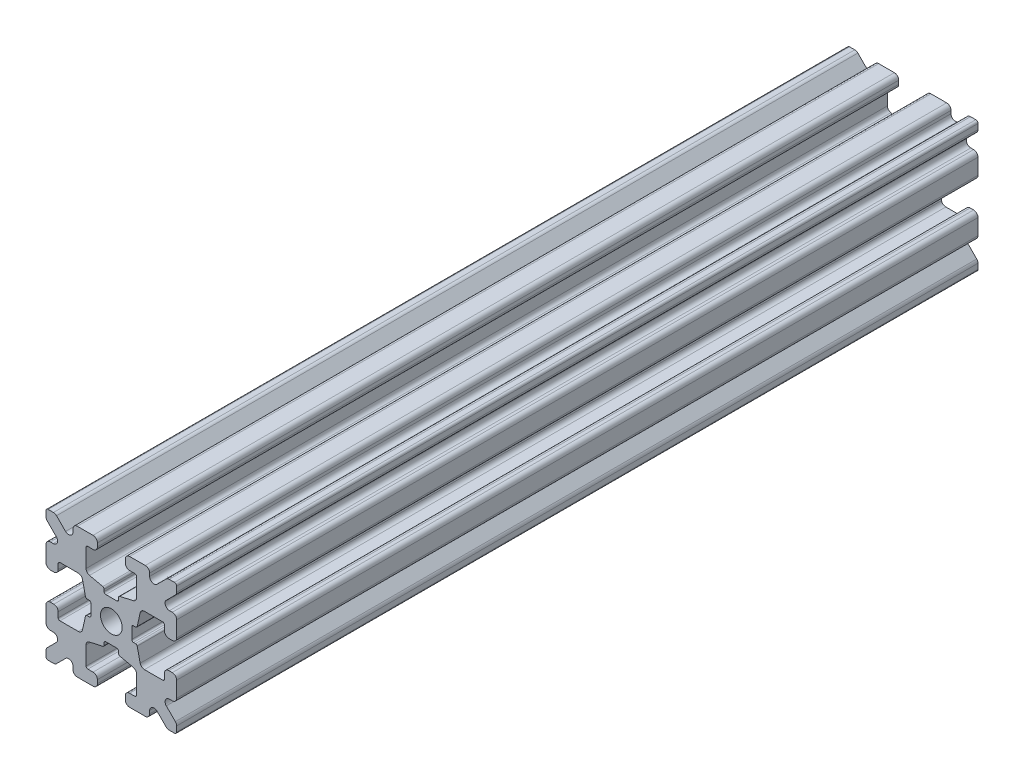
SolidWorks part; units mm, degrees
ref_plane "Front Plane" through (0, 0, 0) normal (0, 0, 1) x (1, 0, 0)
ref_plane "Top Plane" through (0, 0, 0) normal (0, 1, 0) x (1, 0, 0)
ref_plane "Right Plane" through (0, 0, 0) normal (1, 0, 0) x (0, 0, -1)
sketch "Sketch1" plane through (0, 0, 0) normal (0, 0, 1) x (1, 0, 0)
  line L1 (-7.5, -7.5) -> (7.5, -7.5)
  line L2 (-7.5, -7.5) -> (-7.5, 7.5)
  line L3 (-7.5, 7.5) -> (7.5, 7.5)
  line L4 (7.5, -7.5) -> (7.5, 7.5)
  line L5 (-7.5, -7.5) -> (7.5, 7.5) construction
  line L6 (-7.5, 7.5) -> (7.5, -7.5) construction
  circle A0 centre (0, 0) radius 1.25
  point P0 (0, 0)
  dimension "D2" = 2.5
  dimension "D1" = 15
extrude "Boss-Extrude1" add sketch "Sketch1" along normal mid plane 92
fillet "Fillet1" radius 0.25 4 edges at (7.5, -7.5, 0) (-7.5, -7.5, 0) (7.5, 7.5, 0) (-7.5, 7.5, 0)
sketch "Sketch2" plane through (0, 0, 46) normal (0, 0, 1) x (1, 0, 0)
  line L0 (-7.5, 7.25) -> (-7.5, -7.25) construction
  line L1 (-7.5, 1.6) -> (-6.1, 1.6)
  line L2 (-7.5, 1.6) -> (-7.5, -1.6)
  line L3 (-7.5, -1.6) -> (-6.1, -1.6)
  line L4 (-6.1, 1.6) -> (-6.1, 2.9)
  line L5 (0, 0) -> (-12.1036, 0) construction
  line L6 (-6.1, -2.9) -> (-3.4, -2.9)
  line L7 (0, 0) -> (-7.25, 7.25) construction
  line L8 (-6.1, 2.9) -> (-3.4, 2.9)
  line L9 (-3.4, -2.9) -> (-3.4, 2.9)
  line L10 (55, 0) -> (-55, 0) construction
  line L11 (-6.1, -2.9) -> (-6.1, -1.6)
  line L12 (2.9, 6.1) -> (1.6, 6.1)
  line L13 (2.9, 3.4) -> (-2.9, 3.4)
  line L14 (-2.9, 6.1) -> (-2.9, 3.4)
  line L15 (2.9, 6.1) -> (2.9, 3.4)
  line L16 (-1.6, 6.1) -> (-2.9, 6.1)
  line L17 (1.6, 7.5) -> (1.6, 6.1)
  line L18 (-1.6, 7.5) -> (1.6, 7.5)
  line L19 (-1.6, 7.5) -> (-1.6, 6.1)
  line L20 (-1.6, -7.5) -> (-1.6, -6.1)
  line L21 (-1.6, -7.5) -> (1.6, -7.5)
  line L22 (1.6, -7.5) -> (1.6, -6.1)
  line L23 (-1.6, -6.1) -> (-2.9, -6.1)
  line L24 (2.9, -6.1) -> (2.9, -3.4)
  line L25 (-2.9, -6.1) -> (-2.9, -3.4)
  line L26 (2.9, -3.4) -> (-2.9, -3.4)
  line L27 (2.9, -6.1) -> (1.6, -6.1)
  line L28 (6.1, -2.9) -> (6.1, -1.6)
  line L29 (3.4, -2.9) -> (3.4, 2.9)
  line L30 (6.1, 2.9) -> (3.4, 2.9)
  line L31 (6.1, -2.9) -> (3.4, -2.9)
  line L32 (6.1, 1.6) -> (6.1, 2.9)
  line L33 (7.5, -1.6) -> (6.1, -1.6)
  line L34 (7.5, 1.6) -> (7.5, -1.6)
  line L35 (7.5, 1.6) -> (6.1, 1.6)
  dimension "D1" = 3.2
  dimension "D2" = 5.8
  dimension "D3" = 1.4
  dimension "D4" = 2.7
extrude "Cut-Extrude1" cut sketch "Sketch2" against normal through all
sketch "Sketch4" plane through (0, 0, 46) normal (0, 0, 1) x (1, 0, 0)
  line L0 (-3.4, 2.9) -> (-2.75, 0)
  line L1 (55, 0) -> (-55, 0) construction
  line L2 (-2.75, 0) -> (-3.4, -2.9)
  line L3 (-3.4, -2.9) -> (-3.4, 2.9) construction
  line L4 (-3.4, 2.9) -> (-3.4, -2.9)
  line L5 (-2.9, 3.4) -> (0, 2.75)
  line L6 (0, 2.75) -> (2.9, 3.4)
  line L7 (2.9, 3.4) -> (-2.9, 3.4)
  line L8 (3.4, 2.9) -> (2.75, 0)
  line L9 (2.75, 0) -> (3.4, -2.9)
  line L10 (3.4, -2.9) -> (3.4, 2.9)
  line L11 (-2.9, -3.4) -> (0, -2.75)
  line L12 (0, -2.75) -> (2.9, -3.4)
  line L13 (2.9, -3.4) -> (-2.9, -3.4)
  circle A2 centre (0, 0) radius 2.75
  circle A3 centre (0, 0) radius 2.75 construction
  dimension "D1" = 1.5
extrude "Cut-Extrude3" cut sketch "Sketch4" against normal through all
fillet "Fillet3" radius 0.5 16 edges at (-6.1, -1.6, 0) (-7.5, -1.6, 0) (-6.1, 1.6, 0) (-7.5, 1.6, 0) (-1.6, -7.5, 0) (-1.6, -6.1, 0) (1.6, -7.5, 0) (1.6, -6.1, 0) (6.1, -1.6, 0) (7.5, -1.6, 0) (7.5, 1.6, 0) (6.1, 1.6, 0) (1.6, 7.5, 0) (1.6, 6.1, 0) (-1.6, 7.5, 0) (-1.6, 6.1, 0)
fillet "Fillet4" radius 0.5 8 edges at (-3.4, 2.9, 0) (-3.4, -2.9, 0) (2.9, -3.4, 0) (-2.9, -3.4, 0) (3.4, -2.9, 0) (3.4, 2.9, 0) (-2.9, 3.4, 0) (2.9, 3.4, 0)
fillet "Fillet5" radius 3 4 edges at (0, -2.75, 0) (2.75, 0, 0) (-2.75, 0, 0) (0, 2.75, 0)
fillet "Fillet6" radius 0.2 8 edges at (-2.9, -6.1, 0) (2.9, -6.1, 0) (6.1, -2.9, 0) (6.1, 2.9, 0) (2.9, 6.1, 0) (-2.9, 6.1, 0) (-6.1, -2.9, 0) (-6.1, 2.9, 0)
sketch "Sketch5" plane through (0, 0, 46) normal (0, 0, 1) x (1, 0, 0)
  line L0 (0, 0) -> (-7.25, 7.25) construction
  line L1 (-7.5, 6.4393) -> (-5.4607, 4.4)
  line L2 (-6.4393, 7.5) -> (-4.4, 5.4607)
  line L3 (-7.5, 4.4) -> (-5.4607, 4.4)
  line L4 (-3.8003, 2.9) -> (-5.9, 2.9) construction
  line L5 (0, 0) -> (-12.1819, 0) construction
  line L6 (-4.4, 7.5) -> (-4.4, 5.4607)
  line L7 (-2.9, 5.9) -> (-2.9, 3.8003) construction
  line L8 (-7.5, 6.4393) -> (-7.5, 4.4)
  line L9 (-7.5, 7.25) -> (-7.5, 2.1) construction
  line L10 (2.1, -7.5) -> (7.25, -7.5) construction
  line L11 (7.5, -7.25) -> (7.5, -2.1) construction
  line L12 (7.25, 7.5) -> (2.1, 7.5) construction
  line L13 (-2.1, 7.5) -> (-7.25, 7.5) construction
  line L14 (-4.4, 7.5) -> (-6.4393, 7.5)
  line L16 (55, 0) -> (-55, 0) construction
  line L17 (0, 0) -> (0, 10.993) construction
  line L18 (0, -54.6431) -> (0, 54.6431) construction
  line L20 (4.4, 7.5) -> (6.4393, 7.5)
  line L22 (7.5, 6.4393) -> (7.5, 4.4)
  line L23 (4.4, 7.5) -> (4.4, 5.4607)
  line L24 (7.5, 4.4) -> (5.4607, 4.4)
  line L25 (6.4393, 7.5) -> (4.4, 5.4607)
  line L26 (7.5, 6.4393) -> (5.4607, 4.4)
  line L27 (7.5, -6.4393) -> (5.4607, -4.4)
  line L28 (6.4393, -7.5) -> (4.4, -5.4607)
  line L29 (7.5, -4.4) -> (5.4607, -4.4)
  line L30 (4.4, -7.5) -> (4.4, -5.4607)
  line L31 (7.5, -6.4393) -> (7.5, -4.4)
  line L33 (4.4, -7.5) -> (6.4393, -7.5)
  line L36 (-4.4, -7.5) -> (-6.4393, -7.5)
  line L38 (-7.5, -6.4393) -> (-7.5, -4.4)
  line L39 (-4.4, -7.5) -> (-4.4, -5.4607)
  line L40 (-7.5, -4.4) -> (-5.4607, -4.4)
  line L41 (-6.4393, -7.5) -> (-4.4, -5.4607)
  line L42 (-7.5, -6.4393) -> (-5.4607, -4.4)
  dimension "D1" = 1.5
  dimension "D2" = 1.5
  dimension "D3" = 1.5
extrude "Cut-Extrude4" cut sketch "Sketch5" against normal through all
fillet "Fillet8" radius 0.5 24 edges at (-5.4607, 4.4, 0) (-7.5, 4.4, 0) (-5.4607, -4.4, 0) (-7.5, -4.4, 0) (-4.4, -7.5, 0) (-4.4, -5.4607, 0) (4.4, -7.5, 0) (4.4, -5.4607, 0) (5.4607, -4.4, 0) (7.5, -4.4, 0) (7.5, 4.4, 0) (5.4607, 4.4, 0) (4.4, 5.4607, 0) (4.4, 7.5, 0) (-4.4, 5.4607, 0) (-4.4, 7.5, 0) (-6.4393, 7.5, 0) (-7.5, 6.4393, 0) (6.4393, 7.5, 0) (7.5, 6.4393, 0) (6.4393, -7.5, 0) (7.5, -6.4393, 0) (-6.4393, -7.5, 0) (-7.5, -6.4393, 0)
sketch "Sketch6" plane through (0, 0, 46) normal (0, 0, 1) x (1, 0, 0)
  line L0 (0, 0) -> (0, 11.013) construction
  line L1 (0.6561, 2.8971) -> (2.1235, 2.8971) construction
  line L2 (0, -54.6431) -> (0, 54.6431) construction
  line L3 (0, 0) -> (7.25, 7.25) construction
  line L4 (7.5, 0.8255) -> (7.5, -0.8255)
  line L5 (2.3471, 0.8255) -> (7.5, 0.8255)
  line L6 (0, 0) -> (12.4016, 0) construction
  line L7 (0.8255, -7.5) -> (-0.8255, -7.5)
  line L8 (2.3471, -0.8255) -> (2.3471, 0.8255)
  line L9 (0.8255, -2.3471) -> (0.8255, -7.5)
  line L10 (7.5, -0.8255) -> (2.3471, -0.8255)
  line L11 (-7.5, -0.8255) -> (-2.3471, -0.8255)
  line L12 (-2.3471, -0.8255) -> (-2.3471, 0.8255)
  line L13 (-0.8255, -2.3471) -> (0.8255, -2.3471)
  line L14 (-0.8255, 7.5) -> (-0.8255, 2.3471)
  line L15 (-0.8255, 2.3471) -> (0.8255, 2.3471)
  line L16 (-0.8255, -7.5) -> (-0.8255, -2.3471)
  line L17 (0.8255, 2.3471) -> (0.8255, 7.5)
  line L18 (0.8255, 7.5) -> (-0.8255, 7.5)
  line L19 (3.9, 7.5) -> (2.1, 7.5) construction
  line L20 (-2.3471, 0.8255) -> (-7.5, 0.8255)
  line L21 (-7.5, 0.8255) -> (-7.5, -0.8255)
  point P5 (0, -2.5973)
  point P7 (0, 2.5973)
  dimension "D3" = 0.55
  dimension "D1" = 1.651
extrude "Cut-Extrude5" cut sketch "Sketch6" against normal through all
fillet "Fillet10" radius 0.2 16 edges at (-2.935, 0.8255, 0) (-2.935, -0.8255, 0) (2.935, -0.8255, 0) (2.935, 0.8255, 0) (0.8255, 2.935, 0) (-0.8255, 2.935, 0) (-2.3471, 0.8255, 0) (-2.3471, -0.8255, 0) (0.8255, 2.3471, 0) (-0.8255, 2.3471, 0) (2.3471, 0.8255, 0) (2.3471, -0.8255, 0) (0.8255, -2.935, 0) (0.8255, -2.3471, 0) (-0.8255, -2.3471, 0) (-0.8255, -2.935, 0)
